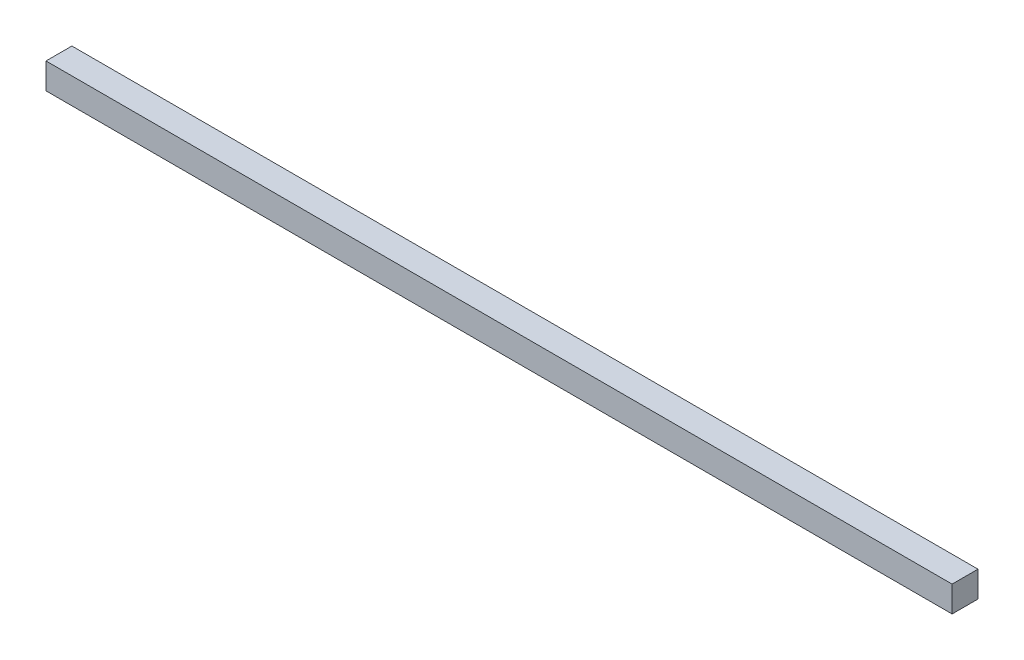
SolidWorks part; units mm, degrees
ref_plane "Front Plane" through (0, 0, 0) normal (0, 0, 1) x (1, 0, 0)
ref_plane "Top Plane" through (0, 0, 0) normal (0, 1, 0) x (1, 0, 0)
ref_plane "Right Plane" through (0, 0, 0) normal (1, 0, 0) x (0, 0, -1)
sketch "Sketch1" plane through (0, 0, 0) normal (0, 0, 1) x (1, 0, 0)
  line L1 (-32.9974, 10.7944) -> (55.9026, 10.7944)
  line L2 (-32.9974, 10.7944) -> (-32.9974, 8.2544)
  line L3 (-32.9974, 8.2544) -> (55.9026, 8.2544)
  line L4 (55.9026, 10.7944) -> (55.9026, 8.2544)
  dimension "D1" = 88.9
  dimension "D2" = 2.54
extrude "Boss-Extrude1" add sketch "Sketch1" along normal blind 2.54
